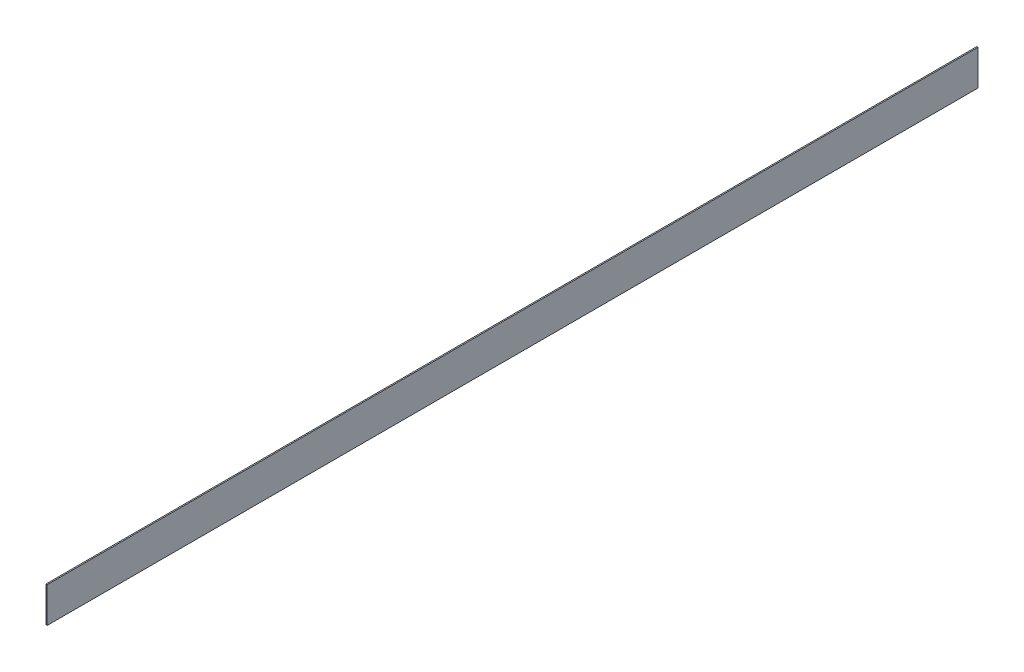
SolidWorks part; units mm, degrees
material "PET"
ref_plane "Front Plane" through (0, 0, 0) normal (0, 0, 1) x (1, 0, 0)
ref_plane "Top Plane" through (0, 0, 0) normal (0, 1, 0) x (1, 0, 0)
ref_plane "Right Plane" through (0, 0, 0) normal (1, 0, 0) x (0, 0, -1)
sketch "Sketch1" plane through (0, 0, 0) normal (1, 0, 0) x (0, 0, -1)
  line L0 (-197.5, 7.5) -> (197.5, -7.5) construction
  line L1 (-197.5, 7.5) -> (197.5, 7.5)
  line L2 (-197.5, 7.5) -> (-197.5, -7.5)
  line L3 (-197.5, -7.5) -> (197.5, -7.5)
  line L4 (197.5, 7.5) -> (197.5, -7.5)
  dimension "D1" = 15
  dimension "D2" = 395
extrude "Boss-Extrude1" add sketch "Sketch1" along normal mid plane 0.5
